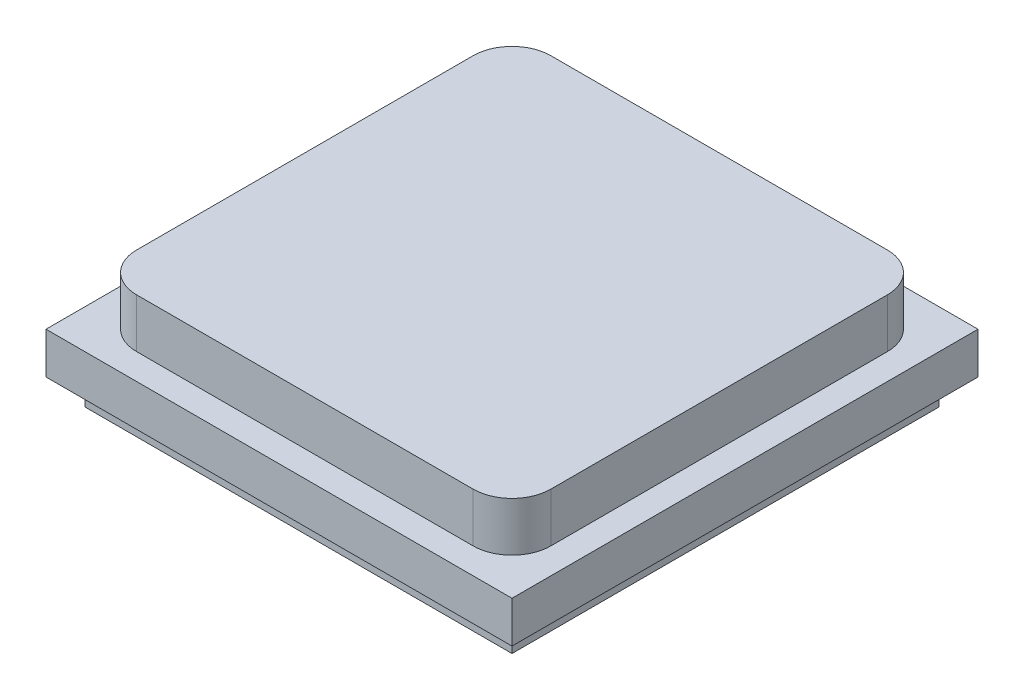
SolidWorks part; units mm, degrees
ref_plane "前视基准面" through (0, 0, 0) normal (0, 0, 1) x (1, 0, 0)
ref_plane "上视基准面" through (0, 0, 0) normal (0, 1, 0) x (1, 0, 0)
ref_plane "右视基准面" through (0, 0, 0) normal (1, 0, 0) x (0, 0, -1)
other "Configuration Table"
sketch "草图1" plane through (0, 0, 0) normal (0, 1, 0) x (1, 0, 0)
  line L1 (9, 9) -> (-9, 9)
  line L2 (9, 9) -> (9, -9)
  line L3 (9, -9) -> (-9, -9)
  line L4 (-9, 9) -> (-9, -9)
  line L5 (9, 9) -> (-9, -9) construction
  line L6 (9, -9) -> (-9, 9) construction
  point P0 (0, 0)
  dimension "D1" = 18
  dimension "D2" = 18
extrude "凸台-拉伸1" add sketch "草图1" along normal blind 1.6
sketch "草图2" plane through (0, 0, 0) normal (0, 1, 0) x (1, 0, 0)
  line L1 (-6.5, 8) -> (6.5, 8)
  line L2 (-8, 6.5) -> (-8, -6.5)
  line L3 (-6.5, -8) -> (6.5, -8)
  line L4 (8, 6.5) -> (8, -6.5)
  line L5 (-8, 8) -> (8, -8) construction
  line L6 (-8, -8) -> (8, 8) construction
  arc A0 (-6.5, 8) -> (-8, 6.5) centre (-6.5, 6.5) ccw
  arc A1 (8, 6.5) -> (6.5, 8) centre (6.5, 6.5) ccw
  arc A2 (-8, -6.5) -> (-6.5, -8) centre (-6.5, -6.5) ccw
  arc A3 (6.5, -8) -> (8, -6.5) centre (6.5, -6.5) ccw
  point P0 (0, 0)
  dimension "D3" = 3
  dimension "D4" = 3
  dimension "D5" = 3
  dimension "D6" = 3
  dimension "D1" = 16
  dimension "D2" = 16
  dimension "D7" = 16
  dimension "D8" = 16
  dimension "D9" = 8
extrude "凸台-拉伸2" add sketch "草图2" along normal blind 1.9 from surface at 1.6 starting at face at (0, 1.6, 0)
sketch "草图3" plane through (0, 0, 0) normal (0, 1, 0) x (1, 0, 0)
  line L1 (-8.25, -8.25) -> (8.25, -8.25)
  line L2 (-8.25, -8.25) -> (-8.25, 8.25)
  line L3 (-8.25, 8.25) -> (8.25, 8.25)
  line L4 (8.25, -8.25) -> (8.25, 8.25)
  line L5 (-8.25, -8.25) -> (8.25, 8.25) construction
  line L6 (-8.25, 8.25) -> (8.25, -8.25) construction
  point P0 (0, 0)
  dimension "D1" = 16.5
  dimension "D2" = 16.5
extrude "凸台-拉伸3" add sketch "草图3" against normal blind 1
